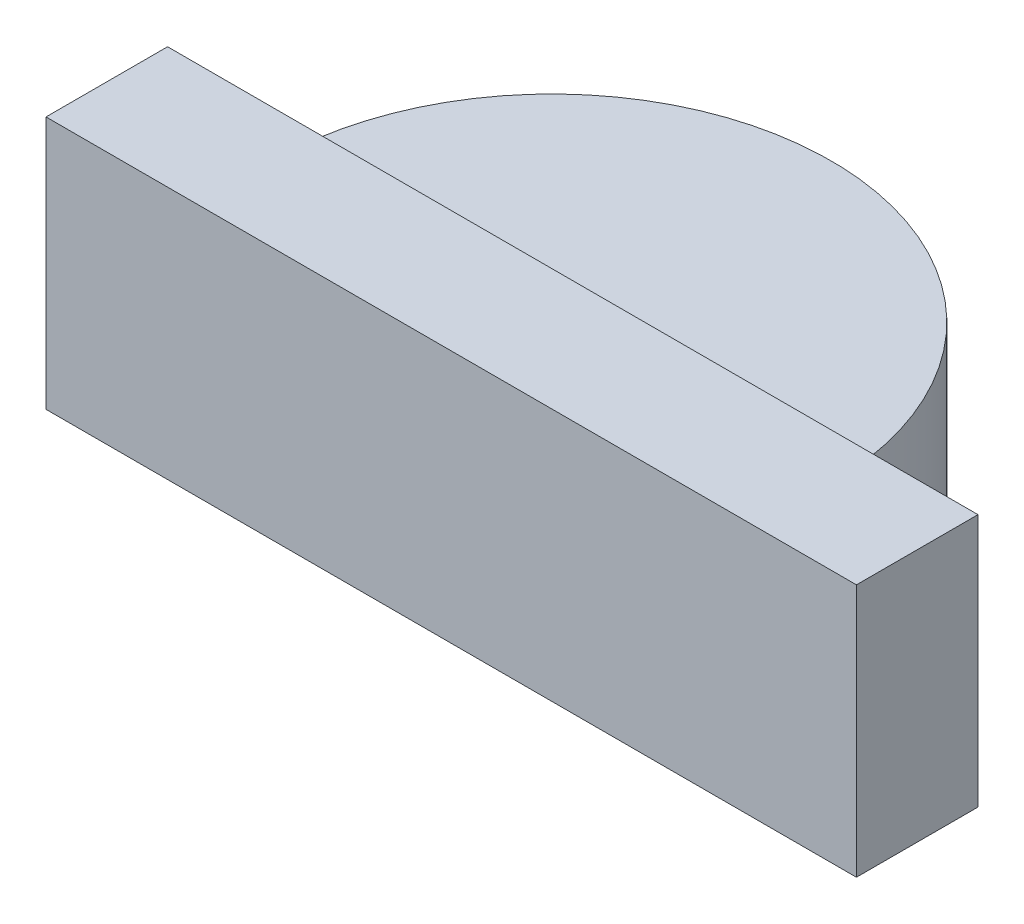
SolidWorks part; units mm, degrees
ref_plane "前视基准面" through (0, 0, 0) normal (0, 0, 1) x (1, 0, 0)
ref_plane "上视基准面" through (0, 0, 0) normal (0, 1, 0) x (1, 0, 0)
ref_plane "右视基准面" through (0, 0, 0) normal (1, 0, 0) x (0, 0, -1)
sketch "草图1" plane through (0, 0, 0) normal (0, 0, 1) x (1, 0, 0)
  line L1 (0, 0) -> (3.2, 0)
  line L2 (0, 0) -> (0, 1)
  line L3 (0, 1) -> (3.2, 1)
  line L4 (3.2, 0) -> (3.2, 1)
  dimension "D1" = 3.2
  dimension "D2" = 1
extrude "凸台-拉伸1" add sketch "草图1" along normal blind 0.48
ref_plane "基准面1" through (0, 0.5, 0) normal (0, -1, 0) x (-1, 0, 0)
sketch "草图2" plane through (0, 0.5, 0) normal (0, -1, 0) x (-1, 0, 0)
  line L0 (-1.6, 0) -> (-1.6, 0.6827) construction
  line L1 (0, 0) -> (-3.2, 0) construction
  line L2 (-1.6, 1.02) -> (-2.3916, 1.02) construction
  line L3 (0, -0.48) -> (-3.2, -0.48) construction
  line L8 (0, 0) -> (-3.2, 0)
  line L9 (-3.2, 0) -> (-3.2, -0.48)
  line L10 (-3.2, -0.48) -> (0, -0.48)
  line L11 (0, -0.48) -> (0, 0)
  line L12 (-0.5, 0) -> (-2.7, 0)
  arc A0 (-0.5, 0) -> (-2.7, 0) centre (-1.6, -0.0831) ccw
  dimension "D1" = 1.5
  dimension "D2" = 2.2
  dimension "D3" = 0
extrude "凸台-拉伸2" add sketch "草图2" along normal mid plane 0.8
